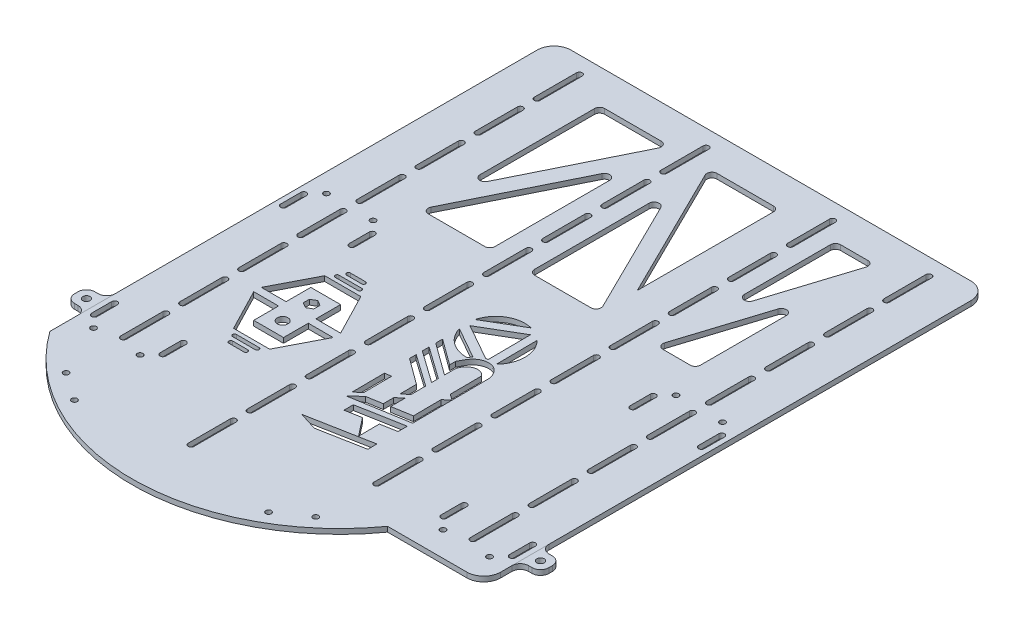
SolidWorks part; units mm, degrees
material "Thornel Mat VMA"
ref_plane "前视基准面" through (0, 0, 0) normal (0, 0, 1) x (1, 0, 0)
ref_plane "上视基准面" through (0, 0, 0) normal (0, 1, 0) x (1, 0, 0)
ref_plane "右视基准面" through (0, 0, 0) normal (1, 0, 0) x (0, 0, -1)
sketch "草图1" plane through (0, 0, 0) normal (0, 1, 0) x (1, 0, 0)
  line L0 (0, 210) -> (50, 210) construction
  line L1 (0, 0) -> (257, 0)
  line L2 (0, 0) -> (0, 350)
  line L3 (0, 350) -> (257, 350)
  line L4 (257, 0) -> (257, 350)
  line L5 (50, 210) -> (50, 60) construction
  line L6 (50, 60) -> (0, 60) construction
  line L7 (128.5, 0) -> (128.5, 350) construction
  line L8 (257, 210) -> (207, 210) construction
  line L9 (207, 210) -> (207, 60) construction
  line L10 (207, 60) -> (257, 60) construction
  line L11 (50, 135) -> (0, 135) construction
  line L12 (25, 210) -> (25, 60) construction
  line L13 (232, 210) -> (232, 60) construction
  line L14 (207, 135) -> (257, 135) construction
  line L15 (45.3, 85) -> (45.3, 73) construction
  line L16 (47, 85) -> (47, 73)
  line L17 (43.6, 85) -> (43.6, 73)
  line L18 (4.7, 85) -> (4.7, 73) construction
  line L19 (3, 85) -> (3, 73)
  line L20 (6.4, 85) -> (6.4, 73)
  line L21 (4.7, 185) -> (4.7, 197) construction
  line L22 (3, 185) -> (3, 197)
  line L23 (6.4, 185) -> (6.4, 197)
  line L24 (45.3, 185) -> (45.3, 197) construction
  line L25 (47, 185) -> (47, 197)
  line L26 (43.6, 185) -> (43.6, 197)
  line L27 (211.7, 85) -> (211.7, 73) construction
  line L28 (210, 85) -> (210, 73)
  line L29 (213.4, 85) -> (213.4, 73)
  line L30 (252.3, 85) -> (252.3, 73) construction
  line L31 (254, 85) -> (254, 73)
  line L32 (250.6, 85) -> (250.6, 73)
  line L33 (252.3, 185) -> (252.3, 197) construction
  line L34 (254, 185) -> (254, 197)
  line L35 (250.6, 185) -> (250.6, 197)
  line L36 (211.7, 185) -> (211.7, 197) construction
  line L37 (210, 185) -> (210, 197)
  line L38 (213.4, 185) -> (213.4, 197)
  arc A0 (47, 85) -> (43.6, 85) centre (45.3, 85) ccw
  arc A1 (43.6, 73) -> (47, 73) centre (45.3, 73) ccw
  arc A2 (3, 85) -> (6.4, 85) centre (4.7, 85) cw
  arc A3 (6.4, 73) -> (3, 73) centre (4.7, 73) cw
  arc A4 (3, 185) -> (6.4, 185) centre (4.7, 185) ccw
  arc A5 (6.4, 197) -> (3, 197) centre (4.7, 197) ccw
  arc A6 (47, 185) -> (43.6, 185) centre (45.3, 185) cw
  arc A7 (43.6, 197) -> (47, 197) centre (45.3, 197) cw
  arc A8 (210, 85) -> (213.4, 85) centre (211.7, 85) cw
  arc A9 (213.4, 73) -> (210, 73) centre (211.7, 73) cw
  arc A10 (254, 85) -> (250.6, 85) centre (252.3, 85) ccw
  arc A11 (250.6, 73) -> (254, 73) centre (252.3, 73) ccw
  arc A12 (254, 185) -> (250.6, 185) centre (252.3, 185) cw
  arc A13 (250.6, 197) -> (254, 197) centre (252.3, 197) cw
  arc A14 (210, 185) -> (213.4, 185) centre (211.7, 185) ccw
  arc A15 (213.4, 197) -> (210, 197) centre (211.7, 197) ccw
  circle A16 centre (245.8, 66) radius 1.65
  circle A17 centre (218.2, 66) radius 1.65
  circle A18 centre (218.2, 204) radius 1.65
  circle A19 centre (245.8, 204) radius 1.65
  circle A20 centre (11.2, 66) radius 1.65
  circle A21 centre (38.8, 66) radius 1.65
  circle A22 centre (11.2, 204) radius 1.65
  circle A23 centre (38.8, 204) radius 1.65
  point P25 (45.3, 79)
  point P32 (4.7, 79)
  point P39 (4.7, 191)
  point P46 (45.3, 191)
  point P54 (211.7, 79)
  point P61 (252.3, 79)
  point P68 (252.3, 191)
  point P75 (211.7, 191)
  dimension "D10" = 27.6
  dimension "D11" = 6
  dimension "D12" = 3.3
  dimension "D1" = 350
  dimension "D2" = 257
  dimension "D3" = 150
  dimension "D4" = 60
  dimension "D5" = 50
  dimension "D6" = 12
  dimension "D7" = 3.4
  dimension "D8" = 100
  dimension "D9" = 44
extrude "凸台-拉伸1" add sketch "草图1" along normal blind 3
sketch "草图2" plane through (0, 0, 0) normal (0, -1, 0) x (1, 0, 0)
  line L0 (0, -350) -> (0, 0) construction
  line L1 (100, -123) -> (100, -8) construction
  line L2 (26.0794, -34.9049) -> (100, -123) construction
  line L3 (100, -123) -> (42.5, -23.4071) construction
  line L4 (157.5, -23.4071) -> (100, -123) construction
  line L5 (100, -123) -> (173.9206, -34.9049) construction
  line L7 (0, 0) -> (257, 0) construction
  line L8 (200, -51.383) -> (257, -51.383)
  line L9 (257, 0) -> (257, -350) construction
  line L10 (257, -51.383) -> (257, 0)
  line L11 (257, 0) -> (0, 0)
  line L12 (0, 0) -> (0, -51.383)
  arc A0 (0, -123) -> (200, -123) centre (100, -123) cw construction
  circle A1 centre (100, -123) radius 115 construction
  circle A2 centre (26.0794, -34.9049) radius 1.65
  circle A3 centre (42.5, -23.4071) radius 1.65
  circle A4 centre (157.5, -23.4071) radius 1.65
  circle A5 centre (173.9206, -34.9049) radius 1.65
  arc A6 (200, -51.383) -> (0, -51.383) centre (100, -123) ccw
  line M1 (0, 0) -> (0, -350)
  line M3 (257, -350) -> (257, 0)
  line M4 (257, 0) -> (0, 0)
  dimension "D1" = 100
  dimension "D2" = 230
  dimension "D5" = 3.3
  dimension "D8" = 246
  dimension "D3" = 10
  dimension "D4" = 10
  dimension "D6" = 30
  dimension "D7" = 30
extrude "切除-拉伸1" cut sketch "草图2" against normal blind 3 contours A6 L11 M1 | A6 L8 M3 M4 | A3 | A5 | A4 | A2
sketch "草图3" plane through (0, 0, 0) normal (0, -1, 0) x (1, 0, 0)
  line L0 (25, -350) -> (25, -51.383) construction
  line L1 (257, -350) -> (0, -350) construction
  line L2 (100, 0) -> (100, -350) construction
  line L3 (175, -350) -> (175, -51.383) construction
  line L4 (232, -51.383) -> (232, -350) construction
  line L5 (200, -51.383) -> (257, -51.383) construction
  line L6 (250.6, -85) -> (250.6, -73) construction
  line L7 (43.6, -85) -> (43.6, -73) construction
  line L8 (25, -340) -> (25, -315) construction
  line L9 (23.3, -340) -> (23.3, -315)
  line L10 (26.7, -340) -> (26.7, -315)
  line L11 (100, -340) -> (100, -315) construction
  line L12 (98.3, -340) -> (98.3, -315)
  line L13 (101.7, -340) -> (101.7, -315)
  line L14 (175, -340) -> (175, -315) construction
  line L15 (173.3, -340) -> (173.3, -315)
  line L16 (176.7, -340) -> (176.7, -315)
  line L17 (232, -340) -> (232, -315) construction
  line L18 (230.3, -340) -> (230.3, -315)
  line L19 (233.7, -340) -> (233.7, -315)
  line L20 (25, -305) -> (25, -280) construction
  line L21 (23.3, -305) -> (23.3, -280)
  line L22 (26.7, -305) -> (26.7, -280)
  line L23 (100, -305) -> (100, -280) construction
  line L24 (98.3, -305) -> (98.3, -280)
  line L25 (101.7, -305) -> (101.7, -280)
  line L26 (175, -305) -> (175, -280) construction
  line L27 (173.3, -305) -> (173.3, -280)
  line L28 (176.7, -305) -> (176.7, -280)
  line L29 (232, -305) -> (232, -280) construction
  line L30 (230.3, -305) -> (230.3, -280)
  line L31 (233.7, -305) -> (233.7, -280)
  line L32 (25, -270) -> (25, -245) construction
  line L33 (23.3, -270) -> (23.3, -245)
  line L34 (26.7, -270) -> (26.7, -245)
  line L35 (100, -270) -> (100, -245) construction
  line L36 (98.3, -270) -> (98.3, -245)
  line L37 (101.7, -270) -> (101.7, -245)
  line L38 (175, -270) -> (175, -245) construction
  line L39 (173.3, -270) -> (173.3, -245)
  line L40 (176.7, -270) -> (176.7, -245)
  line L41 (232, -270) -> (232, -245) construction
  line L42 (230.3, -270) -> (230.3, -245)
  line L43 (233.7, -270) -> (233.7, -245)
  line L44 (25, -235) -> (25, -210) construction
  line L45 (23.3, -235) -> (23.3, -210)
  line L46 (26.7, -235) -> (26.7, -210)
  line L47 (100, -235) -> (100, -210) construction
  line L48 (98.3, -235) -> (98.3, -210)
  line L49 (101.7, -235) -> (101.7, -210)
  line L50 (175, -235) -> (175, -210) construction
  line L51 (173.3, -235) -> (173.3, -210)
  line L52 (176.7, -235) -> (176.7, -210)
  line L53 (232, -235) -> (232, -210) construction
  line L54 (230.3, -235) -> (230.3, -210)
  line L55 (233.7, -235) -> (233.7, -210)
  line L56 (25, -200) -> (25, -175) construction
  line L57 (23.3, -200) -> (23.3, -175)
  line L58 (26.7, -200) -> (26.7, -175)
  line L59 (100, -200) -> (100, -175) construction
  line L60 (98.3, -200) -> (98.3, -175)
  line L61 (101.7, -200) -> (101.7, -175)
  line L62 (175, -200) -> (175, -175) construction
  line L63 (173.3, -200) -> (173.3, -175)
  line L64 (176.7, -200) -> (176.7, -175)
  line L65 (232, -200) -> (232, -175) construction
  line L66 (230.3, -200) -> (230.3, -175)
  line L67 (233.7, -200) -> (233.7, -175)
  line L68 (25, -165) -> (25, -140) construction
  line L69 (23.3, -165) -> (23.3, -140)
  line L70 (26.7, -165) -> (26.7, -140)
  line L71 (100, -165) -> (100, -140) construction
  line L72 (98.3, -165) -> (98.3, -140)
  line L73 (101.7, -165) -> (101.7, -140)
  line L74 (175, -165) -> (175, -140) construction
  line L75 (173.3, -165) -> (173.3, -140)
  line L76 (176.7, -165) -> (176.7, -140)
  line L77 (232, -165) -> (232, -140) construction
  line L78 (230.3, -165) -> (230.3, -140)
  line L79 (233.7, -165) -> (233.7, -140)
  line L80 (25, -130) -> (25, -105) construction
  line L81 (23.3, -130) -> (23.3, -105)
  line L82 (26.7, -130) -> (26.7, -105)
  line L83 (100, -130) -> (100, -105) construction
  line L84 (98.3, -130) -> (98.3, -105)
  line L85 (101.7, -130) -> (101.7, -105)
  line L86 (175, -130) -> (175, -105) construction
  line L87 (173.3, -130) -> (173.3, -105)
  line L88 (176.7, -130) -> (176.7, -105)
  line L89 (232, -130) -> (232, -105) construction
  line L90 (230.3, -130) -> (230.3, -105)
  line L91 (233.7, -130) -> (233.7, -105)
  line L92 (25, -95) -> (25, -70) construction
  line L93 (23.3, -95) -> (23.3, -70)
  line L94 (26.7, -95) -> (26.7, -70)
  line L95 (100, -95) -> (100, -70) construction
  line L96 (98.3, -95) -> (98.3, -70)
  line L97 (101.7, -95) -> (101.7, -70)
  line L98 (175, -95) -> (175, -70) construction
  line L99 (173.3, -95) -> (173.3, -70)
  line L100 (176.7, -95) -> (176.7, -70)
  line L101 (232, -95) -> (232, -70) construction
  line L102 (230.3, -95) -> (230.3, -70)
  line L103 (233.7, -95) -> (233.7, -70)
  line L104 (100, -60) -> (100, -35) construction
  line L105 (98.3, -60) -> (98.3, -35)
  line L106 (101.7, -60) -> (101.7, -35)
  arc A0 (200, -51.383) -> (0, -51.383) centre (100, -123) ccw construction
  arc A1 (23.3, -340) -> (26.7, -340) centre (25, -340) ccw
  arc A2 (26.7, -315) -> (23.3, -315) centre (25, -315) ccw
  arc A3 (98.3, -340) -> (101.7, -340) centre (100, -340) ccw
  arc A4 (101.7, -315) -> (98.3, -315) centre (100, -315) ccw
  arc A5 (173.3, -340) -> (176.7, -340) centre (175, -340) ccw
  arc A6 (176.7, -315) -> (173.3, -315) centre (175, -315) ccw
  arc A7 (230.3, -340) -> (233.7, -340) centre (232, -340) ccw
  arc A8 (233.7, -315) -> (230.3, -315) centre (232, -315) ccw
  arc A9 (23.3, -305) -> (26.7, -305) centre (25, -305) ccw
  arc A10 (26.7, -280) -> (23.3, -280) centre (25, -280) ccw
  arc A11 (98.3, -305) -> (101.7, -305) centre (100, -305) ccw
  arc A12 (101.7, -280) -> (98.3, -280) centre (100, -280) ccw
  arc A13 (173.3, -305) -> (176.7, -305) centre (175, -305) ccw
  arc A14 (176.7, -280) -> (173.3, -280) centre (175, -280) ccw
  arc A15 (230.3, -305) -> (233.7, -305) centre (232, -305) ccw
  arc A16 (233.7, -280) -> (230.3, -280) centre (232, -280) ccw
  arc A17 (23.3, -270) -> (26.7, -270) centre (25, -270) ccw
  arc A18 (26.7, -245) -> (23.3, -245) centre (25, -245) ccw
  arc A19 (98.3, -270) -> (101.7, -270) centre (100, -270) ccw
  arc A20 (101.7, -245) -> (98.3, -245) centre (100, -245) ccw
  arc A21 (173.3, -270) -> (176.7, -270) centre (175, -270) ccw
  arc A22 (176.7, -245) -> (173.3, -245) centre (175, -245) ccw
  arc A23 (230.3, -270) -> (233.7, -270) centre (232, -270) ccw
  arc A24 (233.7, -245) -> (230.3, -245) centre (232, -245) ccw
  arc A25 (23.3, -235) -> (26.7, -235) centre (25, -235) ccw
  arc A26 (26.7, -210) -> (23.3, -210) centre (25, -210) ccw
  arc A27 (98.3, -235) -> (101.7, -235) centre (100, -235) ccw
  arc A28 (101.7, -210) -> (98.3, -210) centre (100, -210) ccw
  arc A29 (173.3, -235) -> (176.7, -235) centre (175, -235) ccw
  arc A30 (176.7, -210) -> (173.3, -210) centre (175, -210) ccw
  arc A31 (230.3, -235) -> (233.7, -235) centre (232, -235) ccw
  arc A32 (233.7, -210) -> (230.3, -210) centre (232, -210) ccw
  arc A33 (23.3, -200) -> (26.7, -200) centre (25, -200) ccw
  arc A34 (26.7, -175) -> (23.3, -175) centre (25, -175) ccw
  arc A35 (98.3, -200) -> (101.7, -200) centre (100, -200) ccw
  arc A36 (101.7, -175) -> (98.3, -175) centre (100, -175) ccw
  arc A37 (173.3, -200) -> (176.7, -200) centre (175, -200) ccw
  arc A38 (176.7, -175) -> (173.3, -175) centre (175, -175) ccw
  arc A39 (230.3, -200) -> (233.7, -200) centre (232, -200) ccw
  arc A40 (233.7, -175) -> (230.3, -175) centre (232, -175) ccw
  arc A41 (23.3, -165) -> (26.7, -165) centre (25, -165) ccw
  arc A42 (26.7, -140) -> (23.3, -140) centre (25, -140) ccw
  arc A43 (98.3, -165) -> (101.7, -165) centre (100, -165) ccw
  arc A44 (101.7, -140) -> (98.3, -140) centre (100, -140) ccw
  arc A45 (173.3, -165) -> (176.7, -165) centre (175, -165) ccw
  arc A46 (176.7, -140) -> (173.3, -140) centre (175, -140) ccw
  arc A47 (230.3, -165) -> (233.7, -165) centre (232, -165) ccw
  arc A48 (233.7, -140) -> (230.3, -140) centre (232, -140) ccw
  arc A49 (23.3, -130) -> (26.7, -130) centre (25, -130) ccw
  arc A50 (26.7, -105) -> (23.3, -105) centre (25, -105) ccw
  arc A51 (98.3, -130) -> (101.7, -130) centre (100, -130) ccw
  arc A52 (101.7, -105) -> (98.3, -105) centre (100, -105) ccw
  arc A53 (173.3, -130) -> (176.7, -130) centre (175, -130) ccw
  arc A54 (176.7, -105) -> (173.3, -105) centre (175, -105) ccw
  arc A55 (230.3, -130) -> (233.7, -130) centre (232, -130) ccw
  arc A56 (233.7, -105) -> (230.3, -105) centre (232, -105) ccw
  arc A57 (23.3, -95) -> (26.7, -95) centre (25, -95) ccw
  arc A58 (26.7, -70) -> (23.3, -70) centre (25, -70) ccw
  arc A59 (98.3, -95) -> (101.7, -95) centre (100, -95) ccw
  arc A60 (101.7, -70) -> (98.3, -70) centre (100, -70) ccw
  arc A61 (173.3, -95) -> (176.7, -95) centre (175, -95) ccw
  arc A62 (176.7, -70) -> (173.3, -70) centre (175, -70) ccw
  arc A63 (230.3, -95) -> (233.7, -95) centre (232, -95) ccw
  arc A64 (233.7, -70) -> (230.3, -70) centre (232, -70) ccw
  arc A65 (98.3, -60) -> (101.7, -60) centre (100, -60) ccw
  arc A66 (101.7, -35) -> (98.3, -35) centre (100, -35) ccw
  point P14 (25, -327.5)
  point P29 (100, -327.5)
  point P34 (175, -327.5)
  point P41 (232, -327.5)
  point P50 (25, -292.5)
  point P59 (100, -292.5)
  point P64 (175, -292.5)
  point P71 (232, -292.5)
  point P78 (25, -257.5)
  point P87 (100, -257.5)
  point P92 (175, -257.5)
  point P99 (232, -257.5)
  point P106 (25, -222.5)
  point P115 (100, -222.5)
  point P120 (175, -222.5)
  point P127 (232, -222.5)
  point P134 (25, -187.5)
  point P143 (100, -187.5)
  point P148 (175, -187.5)
  point P155 (232, -187.5)
  point P162 (25, -152.5)
  point P171 (100, -152.5)
  point P176 (175, -152.5)
  point P183 (232, -152.5)
  point P190 (25, -117.5)
  point P199 (100, -117.5)
  point P204 (175, -117.5)
  point P211 (232, -117.5)
  point P218 (25, -82.5)
  point P227 (100, -82.5)
  point P232 (175, -82.5)
  point P239 (232, -82.5)
  point P246 (100, -47.5)
  dimension "D1" = 18.6
  dimension "D2" = 18.6
  dimension "D3" = 75
  dimension "D4" = 3.4
  dimension "D5" = 25
  dimension "D6" = 10
  dimension "D7" = 3.4
  dimension "D8" = 3.4
  dimension "D9" = 3.4
  dimension "D10" = 10
  dimension "D11" = 10
  dimension "D12" = 10
  dimension "D13" = 25
  dimension "D14" = 25
  dimension "D15" = 25
  dimension "D17" = 10
  dimension "D18" = 3.4
  dimension "D19" = 25
  dimension "D20" = 10
  dimension "D16" = 8
extrude "切除-拉伸2" cut sketch "草图3" against normal through all
sketch "草图4" plane through (0, 0, 0) normal (0, -1, 0) x (1, 0, 0)
  line L0 (47, -223.7) -> (88.3, -223.7)
  line L1 (88.3, -223.7) -> (88.3, -307.4006)
  line L2 (88.3, -307.4006) -> (47, -223.7)
  line L3 (47, -246.2994) -> (88.3, -330)
  line L4 (88.3, -330) -> (47, -330)
  line L5 (47, -330) -> (47, -246.2994)
  line L6 (47, -185) -> (47, -197) construction
  line L7 (98.3, -105) -> (98.3, -130) construction
  line L8 (186.7, -223.7) -> (210, -223.7)
  line L9 (210, -223.7) -> (210, -296.9927)
  line L10 (210, -296.9927) -> (186.7, -223.7)
  line L11 (186.7, -256.7073) -> (210, -330)
  line L12 (210, -330) -> (186.7, -330)
  line L13 (186.7, -330) -> (186.7, -256.7073)
  line L14 (176.7, -165) -> (176.7, -140) construction
  line L15 (210, -85) -> (210, -73) construction
  line L16 (100, -340) -> (100, 0) construction
  line L17 (153, -330) -> (153, -246.2994)
  line L18 (111.7, -330) -> (153, -330)
  line L19 (153, -246.2994) -> (111.7, -330)
  line L20 (111.7, -307.4006) -> (153, -223.7)
  line L21 (111.7, -223.7) -> (111.7, -307.4006)
  line L22 (153, -223.7) -> (111.7, -223.7)
  line L23 (257, -350) -> (0, -350) construction
  arc A4 (200, -51.383) -> (0, -51.383) centre (100, -123) ccw construction
  arc A5 (43.6, -197) -> (47, -197) centre (45.3, -197) ccw construction
  point P13 (45.3, -198.7)
  point P16 (98.3, -117.5)
  dimension "D1" = 10
  dimension "D2" = 20
  dimension "D3" = 25
  dimension "D4" = 10
  dimension "D5" = 10
  dimension "D7" = 10
extrude "切除-拉伸3" cut sketch "草图4" against normal through all
fillet "圆角1" radius 3 17 edges at (186.7, 1.5, -330) (210, 1.5, -330) (210, 1.5, -296.9927) (210, 1.5, -223.7) (186.7, 1.5, -256.7073) (186.7, 1.5, -223.7) (111.7, 1.5, -223.7) (111.7, 1.5, -307.4006) (153, 1.5, -330) (111.7, 1.5, -330) (47, 1.5, -246.2994) (47, 1.5, -223.7) (153, 1.5, -223.7) (88.3, 1.5, -223.7) (47, 1.5, -330) (88.3, 1.5, -307.4006) (88.3, 1.5, -330)
fillet "圆角2" radius 10 3 edges at (257, 1.5, -51.383) (0, 1.5, -350) (257, 1.5, -350)
sketch "草图5" plane through (0, 3, 0) normal (0, 1, 0) x (1, 0, 0)
  line L0 (0, 85) -> (-12, 85)
  line L1 (0, 340) -> (0, 51.383) construction
  line L2 (-12, 85) -> (-12, 73)
  line L3 (-12, 73) -> (0, 73)
  line L4 (0, 85) -> (0, 73)
  line L5 (257, 85) -> (269, 85)
  line L6 (257, 61.383) -> (257, 340) construction
  line L7 (269, 85) -> (269, 73)
  line L8 (269, 73) -> (257, 73)
  line L9 (254, 73) -> (254, 85) construction
  line L10 (-12, 79) -> (0, 79) construction
  line L11 (269, 79) -> (257, 79) construction
  line L12 (257, 73) -> (257, 85)
  line L13 (257, 68) -> (257, 73)
  line L14 (257, 85) -> (257, 90)
  line L15 (0, 68) -> (0, 73)
  line L16 (0, 90) -> (0, 85)
  circle A1 centre (-6, 79) radius 2.15
  circle A2 centre (263, 79) radius 2.15
  arc A3 (-5, 73) -> (0, 68) centre (-5, 68) cw
  arc A4 (-5, 85) -> (0, 90) centre (-5, 90) ccw
  arc A5 (262, 73) -> (257, 68) centre (262, 68) ccw
  arc A6 (262, 85) -> (257, 90) centre (262, 90) cw
  dimension "D2" = 4.3
  dimension "D3" = 4.3
  dimension "D4" = 5
  dimension "D5" = 5
  dimension "D1" = 12
extrude "凸台-拉伸2" add sketch "草图5" against normal blind 3 separate body contours L4 L0 L2 L3 A1 | L3 A3 L15 | A4 L0 L16 | L12 L8 L7 L5 A2 | A5 L8 L13 | L5 A6 L14
fillet "圆角3" radius 5 2 edges at (-12, 1.5, -73) (-12, 1.5, -85)
fillet "圆角4" radius 5 2 edges at (269, 1.5, -85) (269, 1.5, -73)
sketch "草图6" plane through (0, 0, 0) normal (0, -1, 0) x (1, 0, 0)
  line L13 (54.702, -136.5571) -> (54.702, -117.4138)
  line L23 (54.702, -151.2005) -> (72.3459, -151.2005)
  line L26 (74.2115, -161.3255) -> (87.0254, -136.5571)
  line L29 (72.3459, -136.5571) -> (87.0254, -136.5571)
  line L32 (63.524, -146.519) -> (66.6758, -144.6993)
  line L35 (66.6758, -144.6993) -> (66.6758, -141.06)
  line L36 (74.2115, -161.3255) -> (87.0254, -136.5571)
  line L37 (40.0226, -136.5571) -> (52.8365, -161.3255)
  line L38 (66.6758, -141.06) -> (63.524, -139.2403)
  line L39 (72.3459, -136.5571) -> (72.3459, -117.4138)
  line L40 (40.0226, -136.5571) -> (54.702, -136.5571)
  line L41 (52.8365, -161.3255) -> (74.2115, -161.3255)
  line L42 (54.702, -151.2005) -> (54.702, -136.5571)
  line L43 (63.524, -256.7929) -> (63.524, -84.5356) construction
  line L44 (54.702, -117.4138) -> (72.3459, -117.4138)
  line L45 (72.3459, -151.2005) -> (72.3459, -136.5571)
  line L46 (72.3459, -136.5571) -> (87.0254, -136.5571)
  line L47 (60.3722, -144.6993) -> (63.524, -146.519)
  line L48 (40.0226, -136.5571) -> (54.702, -136.5571)
  line L49 (52.8365, -161.3255) -> (74.2115, -161.3255)
  line L50 (60.3722, -141.06) -> (60.3722, -144.6993)
  line L51 (40.0226, -136.5571) -> (52.8365, -161.3255)
  line L52 (63.524, -139.2403) -> (60.3722, -141.06)
  line L53 (56.774, -164.7005) -> (70.274, -164.7005) construction
  line L54 (56.774, -163.5755) -> (70.274, -163.5755)
  line L55 (56.774, -165.8255) -> (70.274, -165.8255)
  line L56 (59.024, -169.2005) -> (68.024, -169.2005) construction
  line L57 (59.024, -168.0755) -> (68.024, -168.0755)
  line L58 (59.024, -170.3255) -> (68.024, -170.3255)
  line L59 (59.024, -99.4138) -> (68.024, -99.4138) construction
  line L60 (59.024, -100.5388) -> (68.024, -100.5388)
  line L61 (59.024, -98.2888) -> (68.024, -98.2888)
  line L62 (56.774, -103.9138) -> (70.274, -103.9138) construction
  line L63 (56.774, -105.0388) -> (70.274, -105.0388)
  line L64 (56.774, -102.7888) -> (70.274, -102.7888)
  line L65 (54.702, -138.0571) -> (5.2906, -138.0571) construction
  line L66 (44.57, -134.327) -> (80.0672, -134.327) construction
  line L67 (72.3459, -132.0968) -> (87.0254, -132.0968)
  line L68 (40.0226, -132.0968) -> (54.702, -132.0968)
  line L69 (40.0226, -132.0968) -> (52.8365, -107.3284)
  line L70 (52.8365, -107.3284) -> (74.2115, -107.3284)
  line L71 (74.2115, -107.3284) -> (87.0254, -132.0968)
  circle A1 centre (63.524, -125.7309) radius 3.15
  circle A10 centre (63.524, -142.8796) radius 3.1518 construction
  arc A11 (56.774, -163.5755) -> (56.774, -165.8255) centre (56.774, -164.7005) ccw
  arc A12 (70.274, -165.8255) -> (70.274, -163.5755) centre (70.274, -164.7005) ccw
  arc A13 (59.024, -168.0755) -> (59.024, -170.3255) centre (59.024, -169.2005) ccw
  arc A14 (68.024, -170.3255) -> (68.024, -168.0755) centre (68.024, -169.2005) ccw
  arc A15 (59.024, -100.5388) -> (59.024, -98.2888) centre (59.024, -99.4138) cw
  arc A16 (68.024, -98.2888) -> (68.024, -100.5388) centre (68.024, -99.4138) cw
  arc A17 (56.774, -105.0388) -> (56.774, -102.7888) centre (56.774, -103.9138) cw
  arc A18 (70.274, -102.7888) -> (70.274, -105.0388) centre (70.274, -103.9138) cw
  point P0 (44.57, -134.327)
  point P12 (63.524, -164.7005)
  point P19 (63.524, -169.2005)
  point P30 (63.524, -142.8796)
  point P46 (63.524, -99.4138)
  point P53 (63.524, -103.9138)
  dimension "D1" = 1.5
extrude "切除-拉伸4" cut sketch "草图6" against normal blind 10 contours A18 L64 A17 L63 | L71 L70 L69 L68 L13 L44 L39 L67 | A1 | L45 L23 L42 L40 L37 L41 L26 L29 | L38 L52 L50 L47 L32 L35 | L60 A16 L61 A15 | L55 A12 L54 A11 | L58 A14 L57 A13
sketch "草图7" plane through (0, 0, 0) normal (0, -1, 0) x (1, 0, 0)
  line L0 (110.0797, -135.1725) -> (430.9058, -135.1725) construction
  line L1 (136.9646, -166.0037) -> (136.9646, -104.0387) construction
  line L2 (149.0979, -166.7237) -> (148.9174, -191.0965)
  line L3 (154.4826, -108.5616) -> (154.523, -103.106)
  line L4 (154.523, -103.106) -> (145.1088, -101.3844)
  line L5 (154.3673, -135.1725) -> (154.5411, -111.7135)
  line L6 (150.872, -132.2425) -> (154.3673, -135.1725)
  line L7 (154.6167, -90.4609) -> (154.6567, -85.0561)
  line L8 (117.212, -83.4083) -> (154.6167, -90.4609)
  line L9 (154.6567, -85.0561) -> (127.926, -80.0161)
  line L10 (154.4146, -135.1737) -> (150.8526, -137.6054)
  line L11 (154.2483, -157.6295) -> (154.4146, -135.1737)
  line L12 (119.8854, -174.0469) -> (138.4548, -163.5085)
  line L13 (144.0662, -191.9641) -> (144.2531, -166.7237)
  line L14 (121.4908, -178.7063) -> (144.0662, -191.9641)
  line L15 (142.988, -166.5063) -> (121.4908, -178.7063)
  line L16 (140.8337, -195.6841) -> (119.8166, -183.3414)
  line L17 (135.7767, -122.9677) -> (135.7041, -132.7661)
  line L18 (139.3946, -125.984) -> (135.7767, -122.9677)
  line L19 (139.3306, -134.6199) -> (139.3946, -125.984)
  line L20 (120.364, -147.9875) -> (139.3306, -134.6199)
  line L21 (120.3935, -144.0017) -> (120.364, -147.9875)
  line L22 (135.7041, -132.7661) -> (120.3935, -144.0017)
  line L23 (124.2306, -129.5956) -> (124.354, -112.9259)
  line L24 (120.5046, -129.0077) -> (124.2306, -129.5956)
  line L25 (120.647, -109.7715) -> (120.5046, -129.0077)
  line L26 (124.354, -112.9259) -> (120.647, -109.7715)
  line L27 (139.3044, -138.1628) -> (120.3369, -151.6411)
  line L28 (139.2745, -142.2039) -> (139.3044, -138.1628)
  line L29 (120.307, -155.6822) -> (139.2745, -142.2039)
  line L30 (120.3369, -151.6411) -> (120.307, -155.6822)
  line L31 (127.4895, -103.6253) -> (154.4826, -108.5616)
  line L32 (127.5311, -98.0173) -> (127.4895, -103.6253)
  line L33 (136.7914, -99.7107) -> (127.5311, -98.0173)
  line L34 (145.2004, -89.0137) -> (136.7914, -99.7107)
  line L35 (145.1088, -101.3844) -> (145.2004, -89.0137)
  line L36 (139.421, -122.4162) -> (139.4853, -113.7436)
  line L37 (135.8045, -119.2148) -> (139.421, -122.4162)
  line L38 (135.8504, -113.0111) -> (135.8045, -119.2148)
  line L39 (126.9244, -111.4956) -> (135.8504, -113.0111)
  line L40 (120.6753, -105.9638) -> (126.9244, -111.4956)
  line L41 (154.5411, -111.7135) -> (120.6753, -105.9638)
  line L42 (150.9946, -115.6976) -> (150.872, -132.2425)
  line L43 (139.4853, -113.7436) -> (150.9946, -115.6976)
  line L44 (127.926, -80.0161) -> (117.212, -83.4083)
  line L45 (120.2777, -159.6374) -> (120.2474, -163.7259)
  line L46 (139.2807, -145.8209) -> (120.2777, -159.6374)
  line L47 (139.2314, -152.4835) -> (139.2807, -145.8209)
  line L48 (150.8526, -137.6054) -> (150.7144, -156.2635)
  line L49 (135.5615, -152.5915) -> (135.5351, -156.1511)
  line L50 (120.2474, -163.7259) -> (135.5615, -152.5915)
  arc A0 (148.9174, -191.0965) -> (149.0979, -166.7237) centre (136.6057, -178.8182) ccw
  arc A1 (137.1072, -161.4377) -> (119.8854, -174.0469) centre (136.6057, -178.8182) ccw
  arc A2 (138.4548, -163.5085) -> (137.1072, -161.4377) centre (145.2783, -157.5939) cw
  arc A3 (119.8166, -183.3414) -> (140.8337, -195.6841) centre (136.6057, -178.8182) ccw
  spline S0 degree 3 poles (135.5351, -156.1511) (136.7188, -158.3576) (138.2343, -161.7566) (142.1464, -164.4851) (145.4103, -165.3968) (148.7238, -165.0663) (151.3065, -163.4952) (153.1454, -160.9719) (154.0324, -158.9586) (154.2483, -157.6295) knots 0 0 0 0 0.283 0.395983 0.522683 0.655085 0.756218 0.850758 1 1 1 1
  spline S1 degree 3 poles (144.2531, -166.7237) (143.8168, -166.7624) (143.3951, -166.6899) (142.988, -166.5063) knots 0 0 0 0 1 1 1 1
  spline S2 degree 3 poles (150.7144, -156.2635) (149.8624, -157.5531) (147.5725, -158.77) (144.3418, -158.4462) (141.2486, -156.6469) (139.7349, -154.318) (139.2314, -152.4835) knots 0 0 0 0 0.301496 0.47403 0.624639 1 1 1 1
  point P0 (108.8045, -137.3398)
extrude "切除-拉伸5" cut sketch "草图7" against normal blind 10
